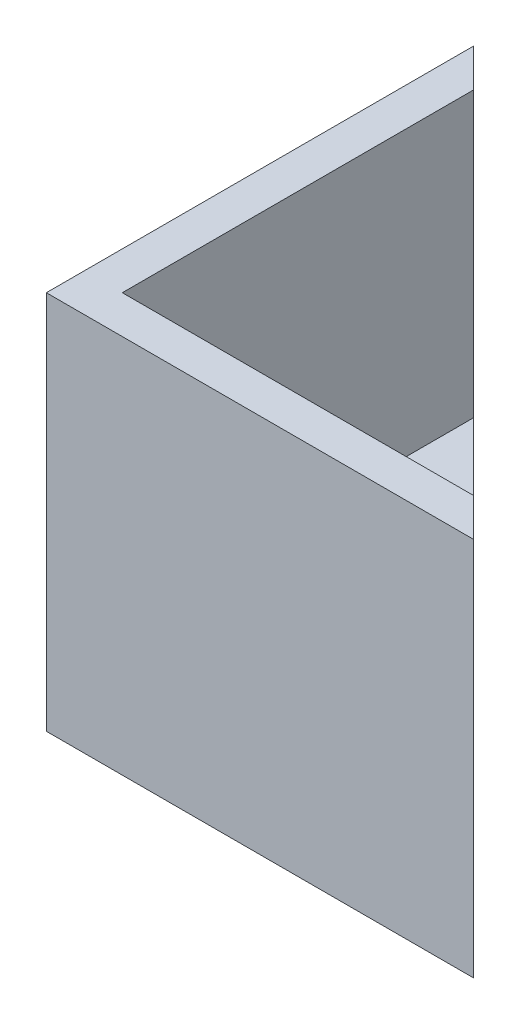
SolidWorks part; units mm, degrees
ref_plane "Front Plane" through (0, 0, 0) normal (0, 0, 1) x (1, 0, 0)
ref_plane "Top Plane" through (0, 0, 0) normal (0, 1, 0) x (1, 0, 0)
ref_plane "Right Plane" through (0, 0, 0) normal (1, 0, 0) x (0, 0, -1)
sketch "Sketch1" plane through (0, 0, 0) normal (0, 1, 0) x (1, 0, 0)
  line L0 (0, 0) -> (45, 0)
  line L1 (45, 0) -> (0, 45)
  line L2 (0, 45) -> (0, 0)
  dimension "D1" = 45
  dimension "D2" = 45
extrude "Boss-Extrude1" add sketch "Sketch1" along normal blind 10.1
sketch "Sketch2" plane through (0, 10.1, 0) normal (0, 1, 0) x (1, 0, 0)
  line L0 (0, 0) -> (45, 0)
  line L1 (45, 0) -> (41, 4)
  line L2 (45, 0) -> (0, 45) construction
  line L3 (41, 4) -> (4, 4)
  line L4 (4, 4) -> (4, 41)
  line L5 (4, 41) -> (0, 45)
  line L6 (0, 45) -> (0, 0)
  dimension "D1" = 4
  dimension "D2" = 4
extrude "Boss-Extrude2" add sketch "Sketch2" along normal blind 29.9
sketch "Sketch3" plane through (0, 10.1, 0) normal (0, 1, 0) x (1, 0, 0)
  line L0 (9, 24.6863) -> (24.6863, 9) construction
  line L1 (12.5355, 28.2218) -> (28.2218, 12.5355)
  line L2 (5.4645, 21.1508) -> (21.1508, 5.4645)
  line L3 (41, 4) -> (4, 41) construction
  line L4 (41, 4) -> (4, 4) construction
  line L5 (4, 4) -> (4, 41) construction
  arc A0 (12.5355, 28.2218) -> (5.4645, 21.1508) centre (9, 24.6863) ccw
  arc A1 (21.1508, 5.4645) -> (28.2218, 12.5355) centre (24.6863, 9) ccw
  point P2 (16.8431, 16.8431)
  dimension "D1" = 10
  dimension "D2" = 3
extrude "Cut-Extrude1" cut sketch "Sketch3" against normal blind 6.1
sketch "Sketch5" plane through (0, 10.1, 0) normal (0, 1, 0) x (1, 0, 0)
  line L0 (9, 24.6863) -> (24.6863, 9) construction
  line L1 (10.9445, 26.6308) -> (26.6308, 10.9445)
  line L2 (7.0555, 22.7417) -> (22.7417, 7.0555)
  line L4 (28.2218, 12.5355) -> (12.5355, 28.2218) construction
  arc A0 (10.9445, 26.6308) -> (7.0555, 22.7417) centre (9, 24.6863) ccw
  arc A1 (22.7417, 7.0555) -> (26.6308, 10.9445) centre (24.6863, 9) ccw
  arc A2 (21.1508, 5.4645) -> (28.2218, 12.5355) centre (24.6863, 9) ccw construction
  point P3 (16.8431, 16.8431)
  dimension "D1" = 5.5
extrude "Cut-Extrude2" cut sketch "Sketch5" against normal through all
